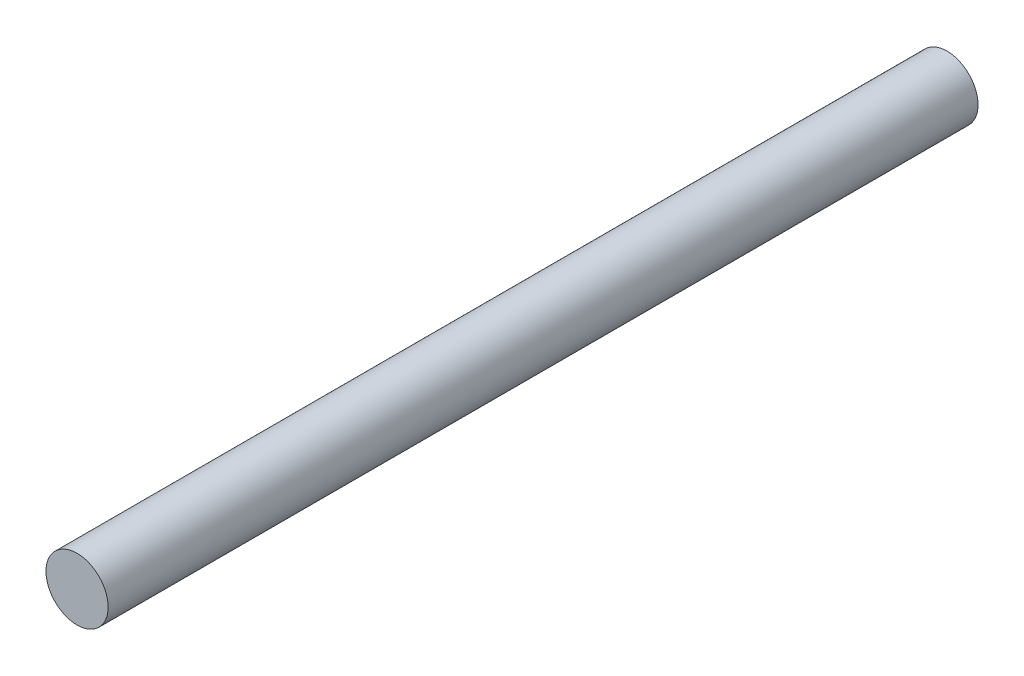
SolidWorks part; units mm, degrees
material "1060 Alloy"
ref_plane "Front Plane" through (0, 0, 0) normal (0, 0, 1) x (1, 0, 0)
ref_plane "Top Plane" through (0, 0, 0) normal (0, 1, 0) x (1, 0, 0)
ref_plane "Right Plane" through (0, 0, 0) normal (1, 0, 0) x (0, 0, -1)
sketch "Sketch1" plane through (0, 0, 0) normal (0, 0, 1) x (1, 0, 0)
  circle A0 centre (0, 0) radius 7.5
  dimension "D1" = 15
extrude "Boss-Extrude1" add sketch "Sketch1" along normal blind 210
